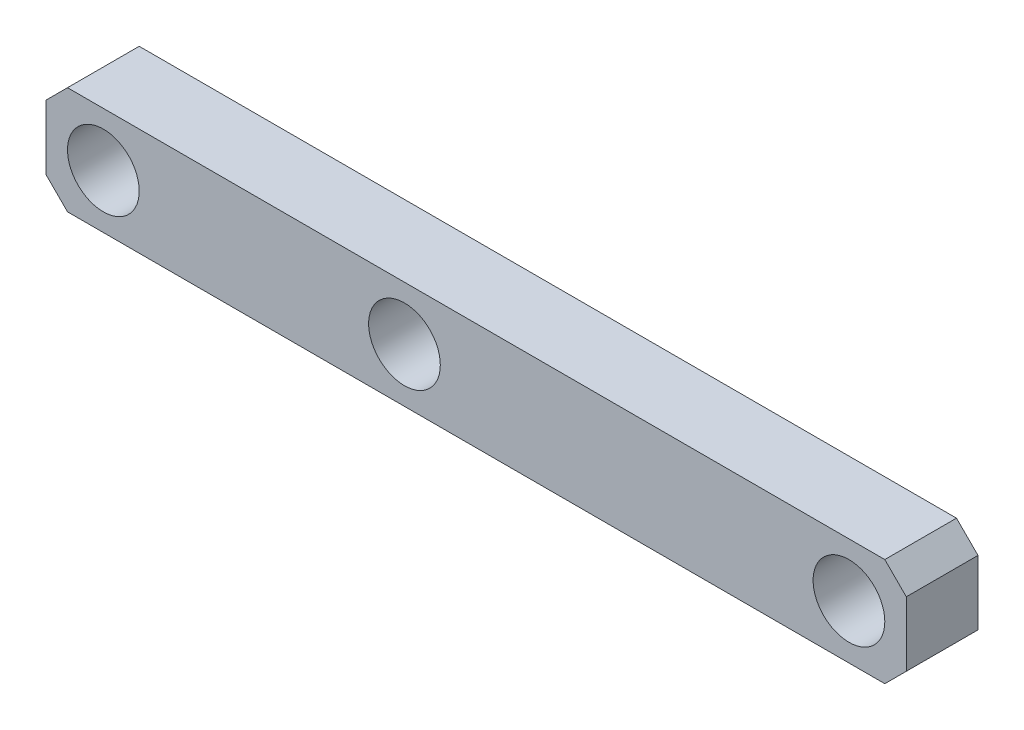
SolidWorks part; units mm, degrees
ref_plane "前视基准面" through (0, 0, 0) normal (0, 0, 1) x (1, 0, 0)
ref_plane "上视基准面" through (0, 0, 0) normal (0, 1, 0) x (1, 0, 0)
ref_plane "右视基准面" through (0, 0, 0) normal (1, 0, 0) x (0, 0, -1)
sketch "草图1" plane through (0, 0, 0) normal (0, 0, 1) x (1, 0, 0)
  line L1 (-72.9904, 13.6495) -> (47.0096, 13.6495)
  line L2 (-72.9904, 13.6495) -> (-72.9904, -1.3505)
  line L3 (-72.9904, -1.3505) -> (47.0096, -1.3505)
  line L4 (47.0096, 13.6495) -> (47.0096, -1.3505)
  line L5 (-12.9904, -1.3505) -> (-12.9904, 13.6495) construction
  line L6 (-72.9904, 6.1495) -> (47.0096, 6.1495) construction
  circle A0 centre (-64.9904, 6.1495) radius 5
  circle A1 centre (39.0096, 6.1495) radius 5
  circle A2 centre (-22.9904, 6.1495) radius 5
  dimension "D3" = 8
  dimension "D4" = 7.5
  dimension "D5" = 7.5
  dimension "D6" = 8
  dimension "D1" = 120
  dimension "D2" = 15
extrude "凸台-拉伸2" add sketch "草图1" along normal blind 10
chamfer "倒角2" distance 3 angle 45 4 edges at (47.0096, -1.3505, 5) (47.0096, 13.6495, 5) (-72.9904, -1.3505, 5) (-72.9904, 13.6495, 5)
